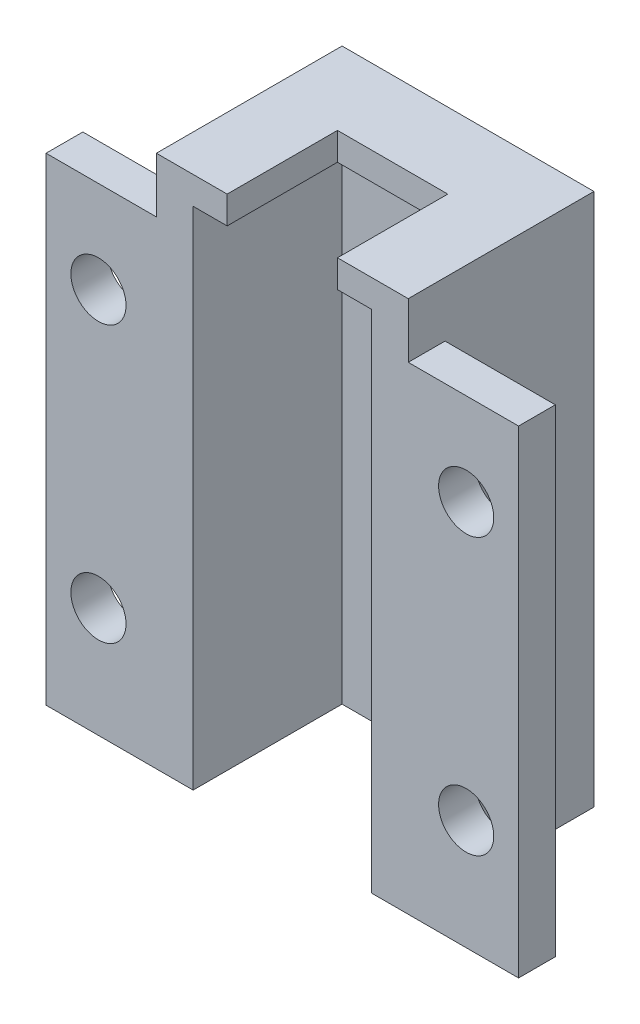
SolidWorks part; units mm, degrees
ref_plane "Front Plane" through (0, 0, 0) normal (0, 0, 1) x (1, 0, 0)
ref_plane "Top Plane" through (0, 0, 0) normal (0, 1, 0) x (1, 0, 0)
ref_plane "Right Plane" through (0, 0, 0) normal (1, 0, 0) x (0, 0, -1)
sketch "Sketch1" plane through (0, 0, 0) normal (0, 1, 0) x (1, 0, 0)
  line L0 (-16.3195, 0) -> (-6.1595, 0)
  line L1 (-6.1595, 0) -> (-6.1595, 10.287)
  line L2 (-6.1595, 10.287) -> (0, 10.287)
  line L3 (0, 10.287) -> (0, 0) construction
  line L4 (-16.3195, 2.54) -> (-8.6995, 2.54)
  line L5 (-8.6995, 2.54) -> (-8.6995, 12.827)
  line L6 (-8.6995, 12.827) -> (0, 12.827)
  line L7 (-16.3195, 2.54) -> (-16.3195, 0)
  line L8 (8.6995, 12.827) -> (0, 12.827)
  line L9 (6.1595, 10.287) -> (0, 10.287)
  line L10 (16.3195, 2.54) -> (16.3195, 0)
  line L11 (8.6995, 2.54) -> (8.6995, 12.827)
  line L12 (16.3195, 2.54) -> (8.6995, 2.54)
  line L13 (6.1595, 0) -> (6.1595, 10.287)
  line L14 (16.3195, 0) -> (6.1595, 0)
  dimension "D1" = 10.287
  dimension "D2" = 6.1595
  dimension "D3" = 10.16
  dimension "D4" = 2.54
extrude "Boss-Extrude1" add sketch "Sketch1" against normal blind 36.83
sketch "Sketch2" plane through (0, 0, 0) normal (0, 1, 0) x (1, 0, 0)
  line L0 (-16.3195, 0) -> (-6.1595, 0) construction
  line L1 (-8.6995, 12.827) -> (8.6995, 12.827)
  line L2 (-8.6995, 12.827) -> (-8.6995, 0)
  line L3 (-8.6995, 0) -> (8.6995, 0) construction
  line L4 (8.6995, 12.827) -> (8.6995, 0)
  line L5 (8.6995, 2.54) -> (8.6995, 12.827) construction
  line L6 (-8.6995, 0) -> (-3.81, 0)
  line L7 (-3.81, 0) -> (-3.81, 7.62)
  line L8 (0, 0) -> (0, 7.62) construction
  line L9 (-3.81, 7.62) -> (3.81, 7.62)
  line L10 (3.81, 0) -> (3.81, 7.62)
  line L11 (8.6995, 0) -> (3.81, 0)
  dimension "D1" = 3.81
  dimension "D2" = 7.62
extrude "Boss-Extrude2" add sketch "Sketch2" against normal blind 1.905
sketch "Sketch3" plane through (0, 0, -2.54) normal (0, 0, -1) x (-1, 0, 0)
  line L0 (-12.7, -10.16) -> (-12.7, -29.21) construction
  line L1 (0, 0) -> (0, -36.2018) construction
  line L2 (12.7, -10.16) -> (12.7, -29.21) construction
  circle A0 centre (-12.7, -10.16) radius 1.905
  circle A1 centre (-12.7, -29.21) radius 1.905
  circle A2 centre (12.7, -29.21) radius 1.905
  circle A3 centre (12.7, -10.16) radius 1.905
  dimension "D1" = 3.81
  dimension "D2" = 19.05
  dimension "D3" = 12.7
  dimension "D4" = 10.16
extrude "Cut-Extrude1" cut sketch "Sketch3" against normal blind 2.54
sketch "Sketch4" plane through (0, 0, -2.54) normal (0, 0, -1) x (-1, 0, 0)
  line L0 (-8.6995, -36.83) -> (-8.6995, 0) construction
  line L1 (-16.3195, 0) -> (-8.6995, 0)
  line L2 (-16.3195, 0) -> (-16.3195, -3.81)
  line L3 (-16.3195, -3.81) -> (-8.6995, -3.81)
  line L4 (-8.6995, 0) -> (-8.6995, -3.81)
  line L5 (8.6995, -36.83) -> (8.6995, 0) construction
  line L6 (16.3195, 0) -> (8.6995, 0)
  line L7 (16.3195, 0) -> (16.3195, -3.81)
  line L8 (16.3195, -3.81) -> (8.6995, -3.81)
  line L9 (8.6995, 0) -> (8.6995, -3.81)
  dimension "D1" = 3.81
extrude "Cut-Extrude2" cut sketch "Sketch4" against normal through all
